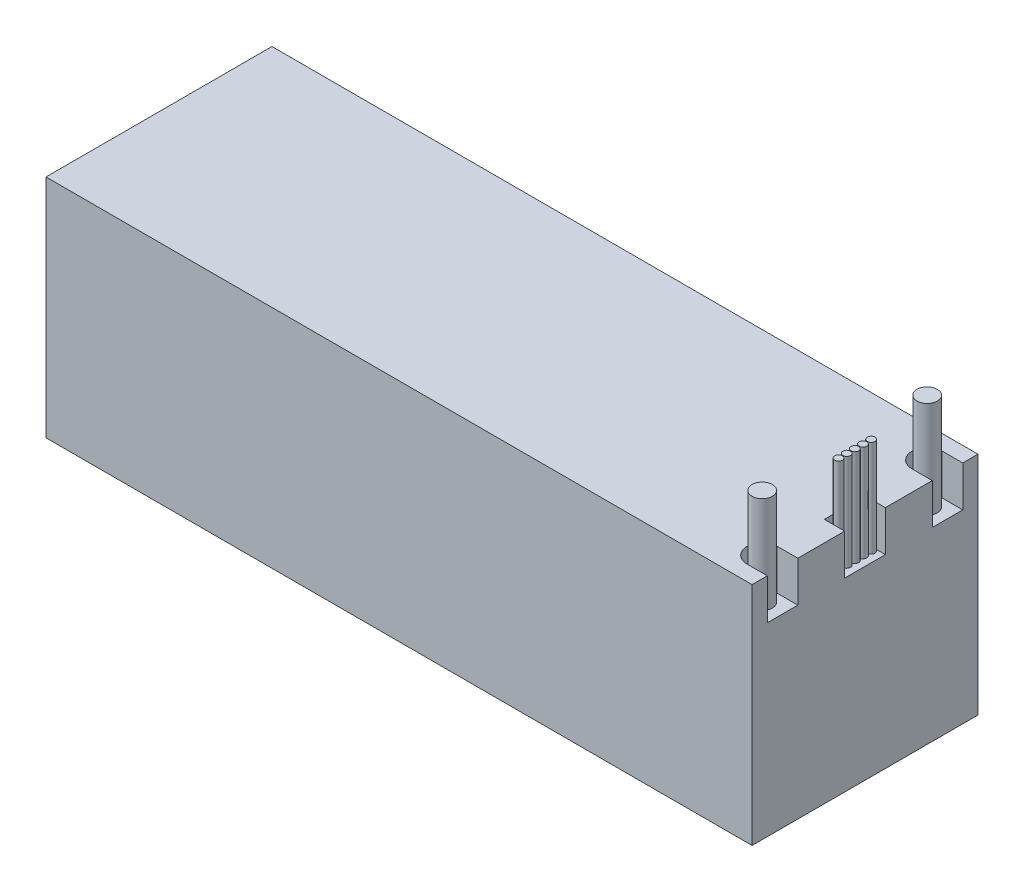
SolidWorks part; units mm, degrees
ref_plane "Front Plane" through (0, 0, 0) normal (0, 0, 1) x (1, 0, 0)
ref_plane "Top Plane" through (0, 0, 0) normal (0, 1, 0) x (1, 0, 0)
ref_plane "Right Plane" through (0, 0, 0) normal (1, 0, 0) x (0, 0, -1)
sketch "Sketch1" plane through (0, 0, 0) normal (0, 0, 1) x (1, 0, 0)
  line L1 (69.4531, 22.225) -> (-69.4531, 22.225)
  line L2 (69.4531, 22.225) -> (69.4531, -22.225)
  line L3 (69.4531, -22.225) -> (-69.4531, -22.225)
  line L4 (-69.4531, 22.225) -> (-69.4531, -22.225)
  line L5 (69.4531, 22.225) -> (-69.4531, -22.225) construction
  line L6 (69.4531, -22.225) -> (-69.4531, 22.225) construction
  point P0 (0, 0)
  dimension "D1" = 44.45
  dimension "D2" = 138.9062
extrude "Boss-Extrude1" add sketch "Sketch1" along normal blind 44.45
sketch "Sketch2" plane through (0, 22.225, 0) normal (0, 1, 0) x (1, 0, 0)
  line L0 (69.4531, -22.225) -> (-69.4531, -22.225) construction
  line L1 (69.4531, -44.45) -> (69.4531, 0) construction
  line L2 (-69.4531, -44.45) -> (-69.4531, 0) construction
  line L3 (62.4531, 0) -> (62.4531, -44.45) construction
  line L4 (69.4531, 0) -> (-69.4531, 0) construction
  line L5 (69.4531, -44.45) -> (-69.4531, -44.45) construction
  line L6 (69.4531, -41.45) -> (62.4531, -41.45) construction
  line L7 (69.4531, -35.45) -> (62.4531, -35.45) construction
  line L8 (69.4531, -38.45) -> (62.4531, -38.45) construction
  line L9 (65.4531, -35.45) -> (69.4531, -35.45)
  line L10 (69.4531, -35.45) -> (69.4531, -41.45)
  line L11 (69.4531, -41.45) -> (65.4531, -41.45)
  line L12 (69.4531, -6) -> (62.4531, -6) construction
  line L13 (69.4531, -9) -> (62.4531, -9) construction
  line L14 (69.4531, -3) -> (62.4531, -3) construction
  line L15 (69.4531, -3) -> (65.4531, -3)
  line L16 (69.4531, -9) -> (69.4531, -3)
  line L17 (65.4531, -9) -> (69.4531, -9)
  line L19 (69.4531, -26.225) -> (65.4531, -26.225)
  line L20 (69.4531, -26.225) -> (69.4531, -18.225)
  line L21 (69.4531, -18.225) -> (65.4531, -18.225)
  line L22 (65.4531, -26.225) -> (65.4531, -18.225)
  circle A0 centre (65.4531, -38.45) radius 3 construction
  arc A1 (65.4531, -35.45) -> (65.4531, -41.45) centre (65.4531, -38.45) ccw
  circle A2 centre (65.4531, -6) radius 3 construction
  arc A3 (65.4531, -9) -> (65.4531, -3) centre (65.4531, -6) cw
  dimension "D1" = 7
  dimension "D2" = 3
  dimension "D3" = 9
  dimension "D4" = 3
  dimension "D5" = 6
  dimension "D6" = 8
  dimension "D7" = 4
  dimension "D8" = 4
extrude "Cut-Extrude1" cut sketch "Sketch2" against normal blind 8
sketch "Sketch3" plane through (0, 14.225, 0) normal (0, 1, 0) x (1, 0, 0)
  line L0 (65.4531, -18.225) -> (65.4531, -26.225) construction
  line L1 (65.4531, -18.225) -> (65.4531, -26.225) construction
  line L2 (67.4531, -18.225) -> (67.4531, -26.225) construction
  line L3 (69.4531, -18.225) -> (65.4531, -18.225) construction
  line L4 (65.4531, -26.225) -> (69.4531, -26.225) construction
  arc A0 (65.4531, -35.45) -> (65.4531, -41.45) centre (65.4531, -38.45) ccw construction
  arc A1 (65.4531, -3) -> (65.4531, -9) centre (65.4531, -6) ccw construction
  arc A2 (65.4531, -35.45) -> (65.4531, -41.45) centre (65.4531, -38.45) ccw construction
  arc A3 (65.4531, -3) -> (65.4531, -9) centre (65.4531, -6) ccw construction
  circle A4 centre (65.4531, -38.45) radius 2
  circle A5 centre (65.4531, -6) radius 2
  circle A6 centre (67.4531, -19.0241) radius 0.75
  circle A7 centre (67.4531, -20.6243) radius 0.75
  circle A8 centre (67.4531, -22.2245) radius 0.75
  circle A9 centre (67.4531, -23.8247) radius 0.75
  circle A10 centre (67.4531, -25.4249) radius 0.75
  dimension "D1" = 4
  dimension "D2" = 1.5
  dimension "D3" = 0.8001
  dimension "D4" = 1.6002
  dimension "D5" = 1.6002
  dimension "D6" = 1.6002
  dimension "D7" = 1.6002
extrude "Boss-Extrude2" add sketch "Sketch3" along normal blind 19.05
equation "\"D4@Sketch2\"=\"D5@Sketch2\"/2"
equation "\"D7@Sketch2\"=\"D6@Sketch2\"/2"
equation "\"D4@Sketch3\"=2*\"D3@Sketch3\""
equation "\"D5@Sketch3\"=\"D4@Sketch3\""
equation "\"D6@Sketch3\"=\"D5@Sketch3\""
equation "\"D7@Sketch3\"=\"D4@Sketch3\""
